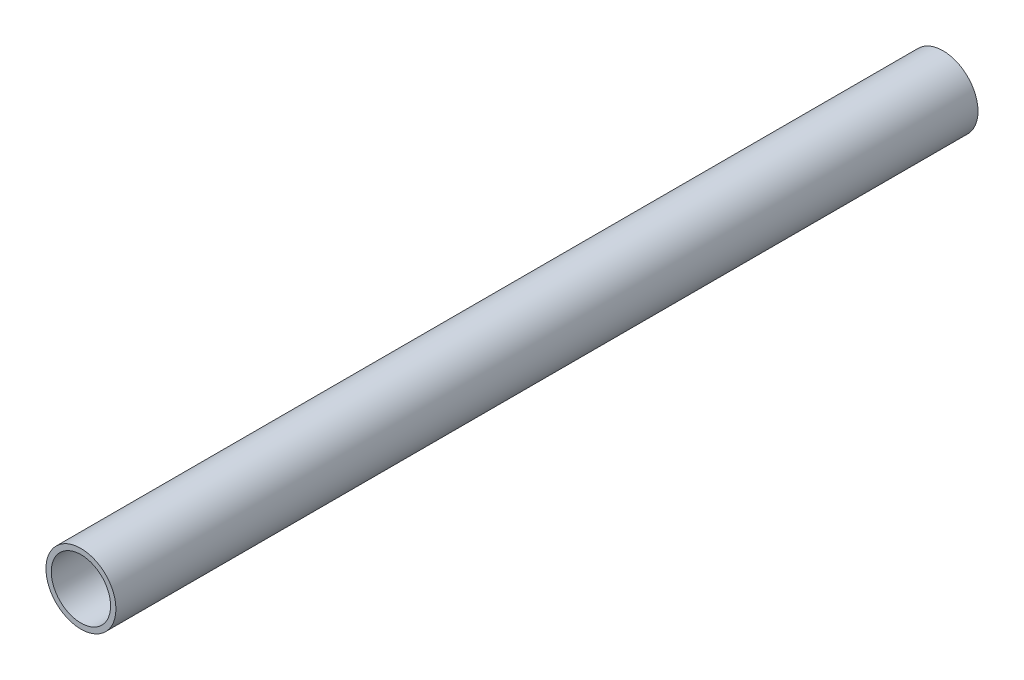
SolidWorks part; units mm, degrees
material "Thornel Mat VMA"
ref_plane "Front Plane" through (0, 0, 0) normal (0, 0, 1) x (1, 0, 0)
ref_plane "Top Plane" through (0, 0, 0) normal (0, 1, 0) x (1, 0, 0)
ref_plane "Right Plane" through (0, 0, 0) normal (1, 0, 0) x (0, 0, -1)
sketch "Sketch1" plane through (0, 0, 0) normal (0, 0, 1) x (1, 0, 0)
  circle A0 centre (0, 0) radius 6.9
  circle A1 centre (0, 0) radius 5.85
  dimension "D1" = 13.8
  dimension "D2" = 11.7
extrude "Boss-Extrude1" add sketch "Sketch1" along normal blind 170
